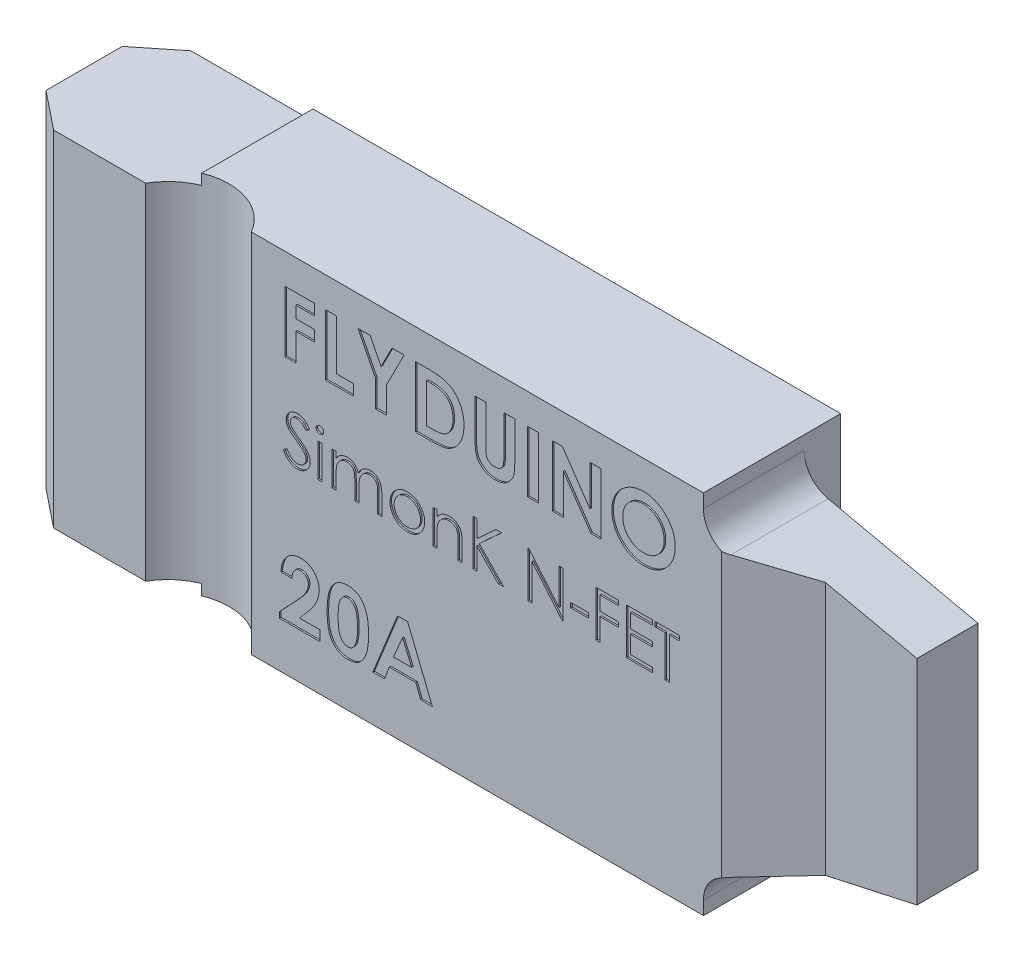
SolidWorks part; units mm, degrees
material "PPS"
ref_plane "Front" through (0, 0, 0) normal (0, 0, 1) x (1, 0, 0)
ref_plane "Top" through (0, 0, 0) normal (0, 1, 0) x (1, 0, 0)
ref_plane "Right" through (0, 0, 0) normal (1, 0, 0) x (0, 0, -1)
sketch "Sketch1" plane through (0, 0, 0) normal (0, 0, 1) x (1, 0, 0)
  line L0 (-17.3, -12) -> (17.3, 12) construction
  line L1 (-17.3, 12) -> (17.3, 12)
  line L2 (-17.3, 12) -> (-17.3, 11.3)
  line L3 (-17.3, -12) -> (17.3, -12)
  line L4 (17.3, 12) -> (17.3, 11.1089)
  line L5 (0, 0) -> (25.8476, 0) construction
  line L6 (18.8716, -9.1554) -> (28.7, -7)
  line L7 (18.8716, 9.1554) -> (28.7, 7)
  line L8 (28.7, -7) -> (28.7, 7)
  line L9 (-27.8, 0) -> (0, 0) construction
  line L10 (-17.3, -11.3) -> (-27.8, -11.3)
  line L11 (17.3, -11.1089) -> (17.3, -12)
  line L12 (-17.3, 11.3) -> (-27.8, 11.3)
  line L13 (-27.8, -11.3) -> (-27.8, 11.3)
  line L14 (-17.3, -11.3) -> (-17.3, -12)
  arc A0 (18.8716, -9.1554) -> (17.3, -11.1089) centre (19.3, -11.1089) ccw
  arc A1 (18.8716, 9.1554) -> (17.3, 11.1089) centre (19.3, 11.1089) cw
  point P11 (28.7, 0)
  point P19 (17.3, -9.5)
  point P22 (17.3, 9.5)
  dimension "D8" = 2
  dimension "D1" = 34.6
  dimension "D2" = 24
  dimension "D3" = 11.4
  dimension "D4" = 19
  dimension "D5" = 14
  dimension "D6" = 22.6
  dimension "D7" = 10.5
extrude "Boss-Extrude1" add sketch "Sketch1" along normal blind 9
sketch "Sketch18" plane through (0, 0, 0) normal (0, 1, 0) x (1, 0, 0)
  line L0 (28.7, -9) -> (28.7, 0) construction
  line L1 (28.7, 0) -> (17.3, 0)
  line L2 (28.7, 0) -> (28.7, -2.4)
  line L3 (28.7, -2.4) -> (17.3, -2.4)
  line L4 (17.3, 0) -> (17.3, -2.4)
  line L5 (28.7, -6.4) -> (22.7, -6.4)
  line L6 (28.7, -6.4) -> (28.7, -9)
  line L7 (28.7, -9) -> (18.5, -9)
  line L8 (22.7, -6.4) -> (18.5, -9)
  line L9 (-17.3, -9) -> (17.3, -9) construction
  line L10 (17.3, -9) -> (17.3, 0) construction
  line L11 (-27.8, -9) -> (-17.3, -9) construction
  line L12 (-19.2641, -9) -> (-12.3359, -9)
  line L13 (-17.3, -9) -> (-17.3, 0) construction
  line L14 (-27.8, -4.5) -> (-39.3619, -4.5) construction
  line L15 (-27.8, -9) -> (-27.8, 0) construction
  line L16 (-27.8, -7) -> (-25.3, -9)
  line L17 (-27.8, -2) -> (-25.3, 0)
  line L18 (-25.3, -9) -> (-27.8, -9)
  line L19 (-25.3, 0) -> (-27.8, 0)
  line L20 (-27.8, -9) -> (-27.8, -7)
  line L21 (-27.8, 0) -> (-27.8, -2)
  arc A0 (-12.3359, -9) -> (-19.2641, -9) centre (-15.8, -11) ccw
  dimension "D5" = 2
  dimension "D6" = 1.5
  dimension "D7" = 4
  dimension "D1" = 2.6
  dimension "D2" = 10.2
  dimension "D3" = 6
  dimension "D4" = 4
  dimension "D8" = 5
  dimension "D9" = 2.5
extrude "Cut-Extrude2" cut sketch "Sketch18" against normal mid plane 200
sketch3d "3DSketch1"
  line L2 (68.0087, -3.1079, 7.4888) -> (71.0087, -3.1079, 7.4888)
  spline S0 degree 3 poles (28.7, -3.6876, 4.2568) (43.1676, -3.9195, 4.2199) (43.8085, -1.9407, 4.2945) (50.2977, -2.124, 5.5091) (63.0861, -2.0924, 7.7472) (61.3367, -3.1079, 7.4888) (68.0087, -3.1079, 7.4888) knots 0 0 0 0 0.190182 0.232615 0.424338 1 1 1 1
  point P0 (28.7, -3.6876, 4.2568)
  dimension "D3" = 3
sketch3d "3DSketch2"
  line L1 (68.1078, 0.8084, 8.2699) -> (71.1078, 0.8084, 8.2699)
  spline S0 degree 3 poles (28.7, 0.7509, 4.2806) (32.0351, 0.8035, 4.4089) (42.7965, 0.2238, 5.1496) (48.5782, 1.3183, 6.6314) (50.526, 0.5327, 6.9865) (61.5911, 0.6945, 7.8439) (59.0599, 0.8084, 8.2699) (68.1078, 0.8084, 8.2699) knots 0 0 0 0 0.215896 0.269114 0.502953 0.578964 1 1 1 1
  point P0 (28.7, 0.7509, 4.2806)
  dimension "D2" = 3
sketch3d "3DSketch3"
  line L1 (68.4684, 4.6645, 8.3171) -> (71.4671, 4.7527, 8.3171)
  spline S0 degree 3 poles (28.7, 4.048, 4.4428) (33.7272, 4.6062, 4.9538) (38.469, 3.9146, 6.5808) (46.6944, 4.6406, 7.2955) (53.6751, 3.7622, 6.582) (61.0565, 4.5829, 6.9586) (63.9733, 4.5323, 8.3171) (68.4684, 4.6645, 8.3171) knots 0 0 0 0 0.29683 0.365307 0.64928 0.716299 1 1 1 1
  point P0 (28.7, 4.048, 4.4428)
  dimension "D2" = 3
sketch3d "3DSketch4"
  line L0 (-78.9795, -14.7687, 8.1475) -> (-81.9795, -14.7687, 8.1475)
  spline S0 degree 3 poles (-27.8, -8.4731, 4.7469) (-42.0092, -9.725, 6.8169) (-36.767, -7.8929, 6.1466) (-55.2764, -10.7273, 7.9966) (-68.4851, -12.9085, 7.2251) (-73.3199, -14.7687, 8.1475) (-78.9795, -14.7687, 8.1475) knots 0 0 0 0 0.357744 0.608768 0.676131 1 1 1 1
  point P0 (-27.8, -8.4731, 4.7469)
  dimension "D1" = 3
sketch3d "3DSketch5"
  line L0 (-79.3227, 6.8144, 7.4609) -> (-82.3206, 6.7033, 7.4609)
  spline S0 degree 3 poles (-27.8, 9.3828, 4.2322) (-42.3127, 8.8082, 5.0619) (-41.4614, 9.0957, 4.8395) (-48.7935, 8.9863, 6.199) (-53.2005, 8.276, 6.4914) (-67.6625, 8.4348, 5.9793) (-72.7936, 7.5298, 7.4609) (-79.3227, 6.8144, 7.4609) knots 0 0 0 0 0.165824 0.229319 0.589879 0.671455 1 1 1 1
  point P0 (-27.8, 9.3828, 4.2322)
  dimension "D3" = 3
sketch3d "3DSketch6"
  line L1 (-148.7534, 3.2066, 7.8844) -> (-151.3182, 2.9458, 9.4186)
  spline S0 degree 3 poles (-27.8, 6.9695, 4.143) (-34.6579, 6.1705, 3.9754) (-44.7261, 4.2862, 4.552) (-48.2337, 3.9587, 3.5338) (-62.2418, 3.155, 4.929) (-73.6545, -0.1213, 4.2659) (-86.9192, 1.5057, 7.829) (-95.2309, 4.2926, 5.8658) (-112.3035, 4.5545, 7.1623) (-132.7676, 5.6565, 5.5256) (-143.1684, 3.7746, 4.5434) (-148.7534, 3.2066, 7.8844) knots 0 0 0 0 0.081296 0.103814 0.211697 0.250533 0.453337 0.508415 0.746235 0.798367 1 1 1 1
  point P1 (-27.8, 6.9695, 4.143)
  dimension "D3" = 3
sketch "Sketch19" plane through (28.7, 0, 0) normal (1, 0, 0) x (0, 0, -1)
  circle A0 centre (-4.2568, -3.6876) radius 1.25
  dimension "D1" = 2.5
sketch "Sketch20" plane through (28.7, 0, 0) normal (1, 0, 0) x (0, 0, -1)
  circle A0 centre (-4.2806, 0.7509) radius 1.25
  dimension "D1" = 2.5
sketch "Sketch21" plane through (28.7, 0, 0) normal (1, 0, 0) x (0, 0, -1)
  circle A0 centre (-4.4428, 4.048) radius 1.25
  dimension "D1" = 2.5
sketch "Sketch23" plane through (-27.8, 0, 0) normal (-1, 0, 0) x (0, 0, 1)
  circle A0 centre (4.7469, -8.4731) radius 1.5
  dimension "D1" = 3
sketch "Sketch24" plane through (-27.8, 0, 0) normal (-1, 0, 0) x (0, 0, 1)
  circle A0 centre (4.2322, 9.3828) radius 1.5
  dimension "D1" = 3
sketch "Sketch25" plane through (-27.8, 0, 0) normal (-1, 0, 0) x (0, 0, 1)
  line L0 (2.8874, 7.1909) -> (5.3987, 6.7481) construction
  line L1 (7, -11.3) -> (7, 11.3) construction
  arc A0 (3.5372, 7.2051) -> (3.4932, 6.9553) centre (2.8874, 7.1909) ccw
  arc A1 (3.4932, 6.9553) -> (4.7488, 6.7339) centre (4.143, 6.9695) ccw
  arc A2 (4.7488, 6.7339) -> (4.7929, 6.9837) centre (5.3987, 6.7481) ccw
  arc A3 (4.7929, 6.9837) -> (3.5372, 7.2051) centre (4.143, 6.9695) ccw
  dimension "D1" = 1.3
  dimension "D2" = 2.55
  dimension "D3" = 100
sweep "Sweep1" [suppressed] add profiles "Sketch21" path "3DSketch3"
sweep "Sweep2" [suppressed] add profiles "Sketch20" path "3DSketch2"
sweep "Sweep3" [suppressed] add profiles "Sketch19" path "3DSketch1"
sweep "Sweep4" [suppressed] add profiles "Sketch23" path "3DSketch4"
sweep "Sweep5" [suppressed] add profiles "Sketch24" path "3DSketch5"
sweep "Sweep6" [suppressed] add profiles "Sketch25" path "3DSketch6"
sketch "Sketch26" plane through (0, 0, 9) normal (0, 0, 1) x (1, 0, 0)
  text T0 "FLYDUINO\r\n\r\n20A" font "Century Gothic" height 4
extrude "Cut-Extrude3" cut sketch "Sketch26" against normal blind 0.1
sketch "Sketch27" plane through (0, 0, 9) normal (0, 0, 1) x (1, 0, 0)
  text T0 "SimonK N-FET" font "Century Gothic" height 3
extrude "Cut-Extrude4" cut sketch "Sketch27" against normal blind 0.1
